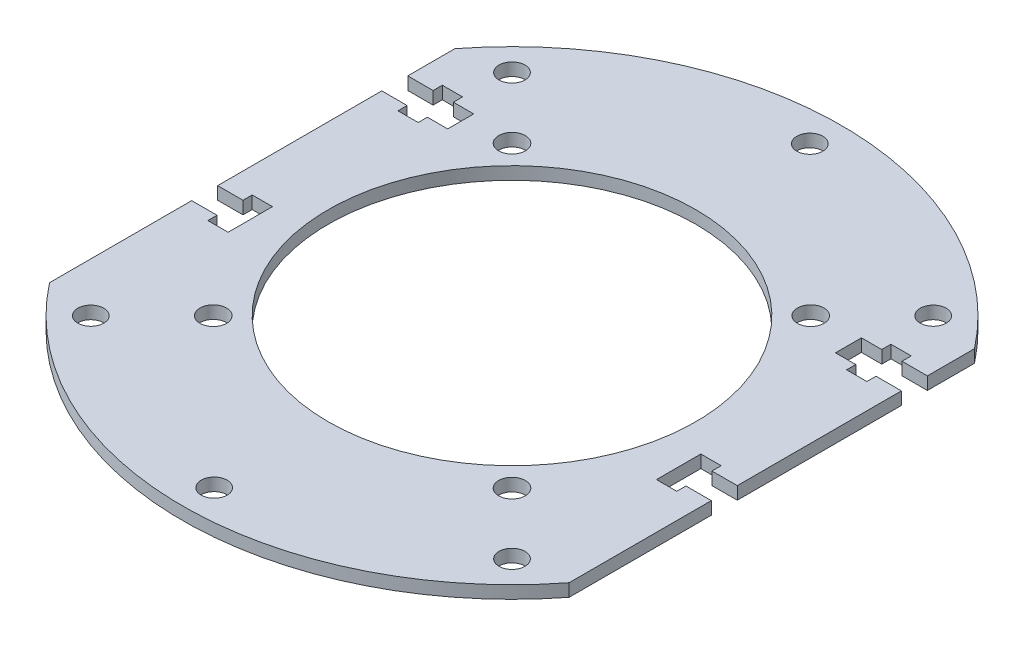
SolidWorks part; units mm, degrees
ref_plane "前视基准面" through (0, 0, 0) normal (0, 0, 1) x (1, 0, 0)
ref_plane "上视基准面" through (0, 0, 0) normal (0, 1, 0) x (1, 0, 0)
ref_plane "右视基准面" through (0, 0, 0) normal (1, 0, 0) x (0, 0, -1)
sketch "草图1" plane through (0, 0, 0) normal (0, 1, 0) x (1, 0, 0)
  line L0 (37, -9.55) -> (37, -11)
  line L1 (23.57, 23.57) -> (-23.57, 23.57) construction
  line L2 (23.57, 23.57) -> (23.57, -23.57) construction
  line L3 (23.57, -23.57) -> (-23.57, -23.57) construction
  line L4 (-23.57, 23.57) -> (-23.57, -23.57) construction
  line L5 (37, -11) -> (33.8, -11)
  line L6 (33.8, -11) -> (33.8, -9.55)
  line L7 (33.8, -5.45) -> (33.8, -4)
  line L8 (37, -4) -> (37, -5.45)
  line L9 (33.8, -4) -> (37, -4)
  line L12 (37, -4) -> (37, 26) construction
  line L13 (37, 20.45) -> (37, 19)
  line L14 (37, 19) -> (33.8, 19)
  line L15 (33.8, 19) -> (33.8, 20.45)
  line L16 (33.8, 24.55) -> (33.8, 26)
  line L17 (37, 26) -> (37, 24.55)
  line L18 (33.8, 26) -> (37, 26)
  line L21 (0, -47) -> (0, -44.95) construction
  line L22 (-37, -4) -> (-37, 26) construction
  line L25 (-33.8, 26) -> (-37, 26)
  line L26 (-37, 26) -> (-37, 24.55)
  line L27 (-33.8, 24.55) -> (-33.8, 26)
  line L28 (-33.8, 19) -> (-33.8, 20.45)
  line L29 (-37, 19) -> (-33.8, 19)
  line L30 (-37, 20.45) -> (-37, 19)
  line L33 (-33.8, -4) -> (-37, -4)
  line L34 (-37, -4) -> (-37, -5.45)
  line L35 (-33.8, -5.45) -> (-33.8, -4)
  line L36 (-33.8, -11) -> (-33.8, -9.55)
  line L37 (-37, -11) -> (-33.8, -11)
  line L38 (-37, -9.55) -> (-37, -11)
  line L39 (37, 24.55) -> (41, 24.55)
  line L40 (41, 24.55) -> (41, 20.45)
  line L41 (41, 20.45) -> (37, 20.45)
  line L42 (33.8, 24.55) -> (30.6, 24.55)
  line L43 (30.6, 24.55) -> (30.6, 20.45)
  line L44 (30.6, 20.45) -> (33.8, 20.45)
  line L45 (37, -5.45) -> (41, -5.45)
  line L46 (41, -5.45) -> (41, -9.55)
  line L47 (41, -9.55) -> (37, -9.55)
  line L48 (33.8, -9.55) -> (30.6, -9.55) construction
  line L49 (30.6, -9.55) -> (30.6, -5.45) construction
  line L50 (30.6, -5.45) -> (33.8, -5.45) construction
  line L51 (-37, 24.55) -> (-41, 24.55)
  line L52 (-41, 24.55) -> (-41, 20.45)
  line L53 (-41, 20.45) -> (-37, 20.45)
  line L54 (-37, -5.45) -> (-41, -5.45)
  line L55 (-41, -5.45) -> (-41, -9.55)
  line L56 (-41, -9.55) -> (-37, -9.55)
  line L57 (-33.8, -5.45) -> (-30.6, -5.45) construction
  line L58 (-30.6, -5.45) -> (-30.6, -9.55) construction
  line L59 (-30.6, -9.55) -> (-33.8, -9.55) construction
  line L60 (-33.8, 24.55) -> (-30.6, 24.55)
  line L61 (-30.6, 24.55) -> (-30.6, 20.45)
  line L62 (-30.6, 20.45) -> (-33.8, 20.45)
  line L63 (-33.8, -9.55) -> (-33.8, -5.45)
  line L64 (33.8, -9.55) -> (33.8, -5.45)
  circle A0 centre (0, 0) radius 29
  circle A1 centre (0, 0) radius 52
  circle A2 centre (47, 0) radius 2.05
  circle A3 centre (33.234, -33.234) radius 2.05
  circle A4 centre (0, -47) radius 2.05
  circle A5 centre (-33.234, -33.234) radius 2.05
  circle A6 centre (-47, 0) radius 2.05
  circle A7 centre (-33.234, 33.234) radius 2.05
  circle A8 centre (0, 47) radius 2.05
  circle A9 centre (33.234, 33.234) radius 2.05
  circle A10 centre (0, 0) radius 43 construction
  circle A11 centre (-23.57, 23.57) radius 2.1
  circle A12 centre (-23.57, -23.57) radius 2.1
  circle A13 centre (23.57, -23.57) radius 2.1
  circle A14 centre (23.57, 23.57) radius 2.1
  circle A15 centre (0, 0) radius 25 construction
  circle A16 centre (0, 0) radius 9.5 construction
  point P6 (52, 0)
  point P9 (43, 0)
  dimension "D1" = 58
  dimension "D2" = 86
  dimension "D3" = 4
  dimension "D4" = 4.1
  dimension "D6" = 30
  dimension "D7" = 5
  dimension "D5" = 8
extrude "凸台-拉伸1" add sketch "草图1" along normal blind 2
sketch "草图2" plane through (0, 2, 0) normal (0, 1, 0) x (1, 0, 0)
  line L1 (-41, -55.0176) -> (41, -55.0176)
  line L2 (-41, -55.0176) -> (-41, 55.0176)
  line L3 (-41, 55.0176) -> (41, 55.0176)
  line L4 (41, -55.0176) -> (41, 55.0176)
  line L5 (-41, -55.0176) -> (41, 55.0176) construction
  line L6 (-41, 55.0176) -> (41, -55.0176) construction
  point P0 (0, 0)
  dimension "D1" = 82
extrude "切除-拉伸-薄壁1" cut sketch "草图2" against normal blind 4 thin
